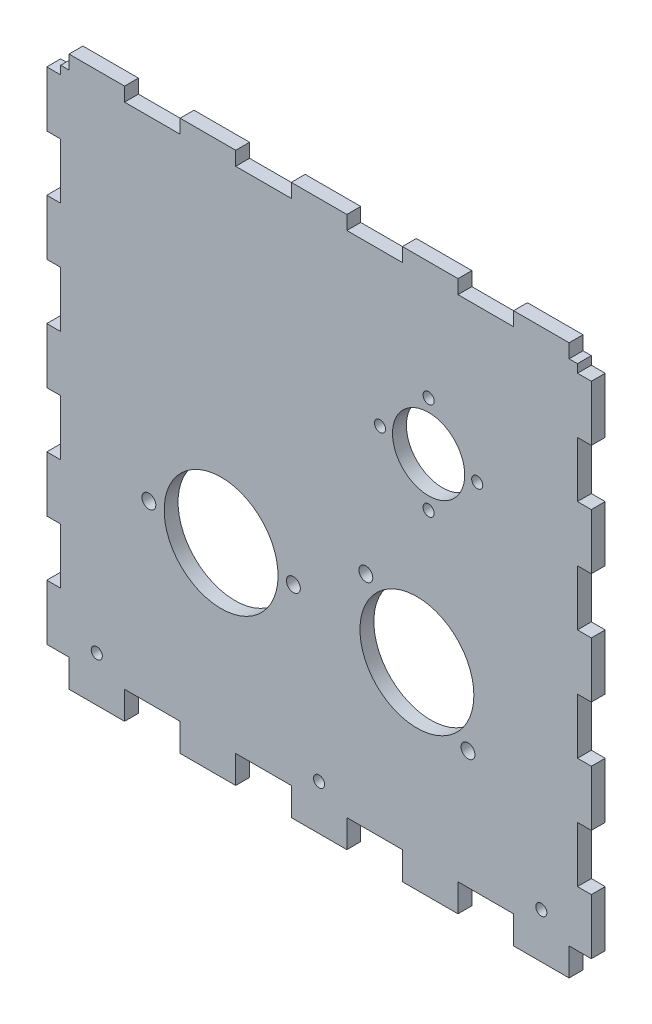
SolidWorks part; units mm, degrees
ref_plane "정면" through (0, 0, 0) normal (0, 0, 1) x (1, 0, 0)
ref_plane "윗면" through (0, 0, 0) normal (0, 1, 0) x (1, 0, 0)
ref_plane "우측면" through (0, 0, 0) normal (1, 0, 0) x (0, 0, -1)
sketch "스케치1" plane through (0, 0, 0) normal (0, 0, 1) x (1, 0, 0)
  line L0 (-35.25, 48.411) -> (-35.25, -111.4061) construction
  line L1 (-93, 91.5) -> (93, 91.5)
  line L2 (-93, 91.5) -> (-93, -91.5)
  line L3 (-93, -91.5) -> (93, -91.5)
  line L4 (93, 91.5) -> (93, -91.5)
  line L5 (-93, 91.5) -> (93, -91.5) construction
  line L6 (-93, -91.5) -> (93, 91.5) construction
  line L7 (39.4226, 64.8355) -> (39.4226, -71.9738) construction
  line L8 (0, 68.0997) -> (0, -64.9282) construction
  line L9 (67.9316, -30.5) -> (15.9316, -30.5) construction
  line L10 (11.3218, -6.6001) -> (50.8051, -46.0834) construction
  circle A1 centre (-35.25, -28.5) radius 20.5
  circle A4 centre (-61.25, -28.5) radius 2.5
  circle A5 centre (-9.25, -28.5) radius 2.5
  circle A6 centre (39.4226, 36.5) radius 21 construction
  circle A9 centre (35.2216, -30.5) radius 20.5
  circle A10 centre (16.8368, -12.1152) radius 2.5
  circle A11 centre (53.6064, -48.8848) radius 2.5
  circle A12 centre (39.4226, 36.5) radius 17.5 construction
  circle A13 centre (39.4226, 19) radius 2
  circle A14 centre (39.4226, 36.5) radius 13
  circle A18 centre (21.9226, 36.5) radius 2
  circle A19 centre (39.4226, 54) radius 2
  circle A20 centre (56.9226, 36.5) radius 2
  point P0 (0, 0)
  point P44 (39.4226, 36.5)
  dimension "D3" = 41
  dimension "D8" = 52
  dimension "D9" = 5
  dimension "D10" = 55
  dimension "D11" = 42
  dimension "D12" = 4
  dimension "D14" = 41
  dimension "D15" = 70.5
  dimension "D17" = 5
  dimension "D20" = 26
  dimension "D1" = 183
  dimension "D2" = 186
  dimension "D4" = 3.5
  dimension "D5" = 63
  dimension "D6" = 99
  dimension "D7" = 35.25
  dimension "D13" = 61
  dimension "D16" = 45
  dimension "D18" = 26
  dimension "D19" = 26
  dimension "D21" = 4
extrude "보스-돌출1" add sketch "스케치1" along normal blind 5
sketch "스케치2" plane through (0, 0, 5) normal (0, 0, 1) x (1, 0, 0)
  line L1 (-93, -91.5) -> (-98, -91.5)
  line L2 (-93, -91.5) -> (-93, -71.5)
  line L3 (-93, -71.5) -> (-98, -71.5)
  line L4 (-98, -91.5) -> (-98, -71.5)
  dimension "D1" = 5
  dimension "D2" = 20
extrude "보스-돌출2" add sketch "스케치2" against normal up to surface (5 mm away) up to face at (0, 0, 0)
pattern_linear "선형 패턴1" count 5 spacing 40 along (0, 1, 0) of "보스-돌출2"
mirror "대칭 복사1" about plane through (0, 0, 0) normal (1, 0, 0) of "선형 패턴1", "보스-돌출2"
sketch "스케치3" plane through (0, 0, 5) normal (0, 0, 1) x (1, 0, 0)
  line L0 (93, 91.5) -> (-93, 91.5) construction
  line L1 (10, 91.5) -> (-10, 91.5)
  line L2 (10, 91.5) -> (10, 96.5)
  line L3 (10, 96.5) -> (-10, 96.5)
  line L4 (-10, 91.5) -> (-10, 96.5)
  line L5 (0, 262.1917) -> (0, -69.1917) construction
  point P9 (0, 96.5)
  dimension "D1" = 20
  dimension "D2" = 5
extrude "보스-돌출3" add sketch "스케치3" against normal up to surface (5 mm away) up to face at (0, 7.65, 0)
pattern_linear "선형 패턴2" count 3 spacing 40 along (1, 0, 0) of "보스-돌출3"
pattern_linear "선형 패턴3" count 3 spacing 40 along (-1, 0, 0) of "보스-돌출3"
sketch "스케치4" plane through (0, 0, 5) normal (0, 0, 1) x (1, 0, 0)
  line L0 (-98, -91.5) -> (98, -91.5) construction
  line L1 (-10, -91.5) -> (10, -91.5)
  line L2 (-10, -91.5) -> (-10, -101.5)
  line L3 (-10, -101.5) -> (10, -101.5)
  line L4 (10, -91.5) -> (10, -101.5)
  line L5 (0, -83.6889) -> (0, -110.8852) construction
  dimension "D1" = 20
  dimension "D2" = 10
extrude "보스-돌출4" add sketch "스케치4" against normal up to surface (5 mm away) up to face at (0, 36.4333, 0)
pattern_linear "선형 패턴4" count 3 spacing 40 along (1, 0, 0) of "보스-돌출4"
pattern_linear "선형 패턴5" count 3 spacing 40 along (-1, 0, 0) of "선형 패턴4"
sketch "스케치5" plane through (0, 0, 0) normal (0, 0, -1) x (-1, 0, 0)
  line L0 (0, -66.2628) -> (0, -108.7434) construction
  line L1 (-10, -91.5) -> (-30, -91.5) construction
  circle A0 centre (0, -85.2) radius 2
  dimension "D1" = 4
  dimension "D2" = 6.3
extrude "컷-돌출1" cut sketch "스케치5" against normal up to next
pattern_linear "선형 패턴6" count 2 spacing 80 along (1, 0, 0) of "컷-돌출1"
pattern_linear "선형 패턴7" count 2 spacing 80 along (-1, 0, 0) of "컷-돌출1"
